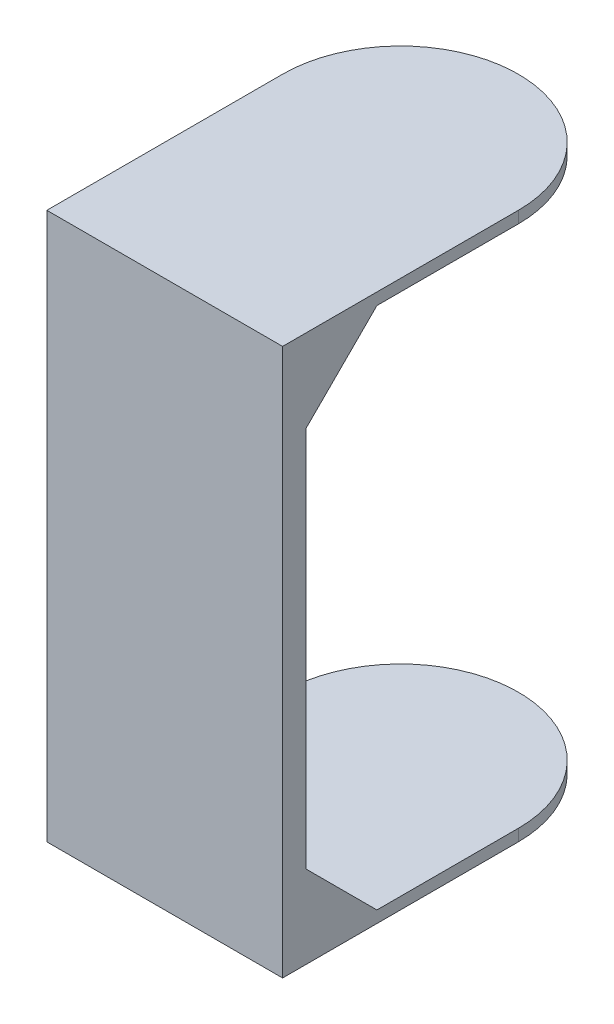
SolidWorks part; units mm, degrees
ref_plane "Front Plane" through (0, 0, 0) normal (0, 0, 1) x (1, 0, 0)
ref_plane "Top Plane" through (0, 0, 0) normal (0, 1, 0) x (1, 0, 0)
ref_plane "Right Plane" through (0, 0, 0) normal (1, 0, 0) x (0, 0, -1)
sketch "Plate Sketch" plane through (0, 0, 0) normal (0, 0, 1) x (1, 0, 0)
  line L1 (-50, 111) -> (50, 111)
  line L2 (-50, 111) -> (-50, -111)
  line L3 (-50, -111) -> (50, -111)
  line L4 (50, 111) -> (50, -111)
  line L5 (-50, 111) -> (50, -111) construction
  line L6 (-50, -111) -> (50, 111) construction
  point P0 (0, 0)
  dimension "D1" = 100
  dimension "D2" = 222
extrude "Plate Extrude" add sketch "Plate Sketch" against normal blind 10
sketch "Primary Support Sketch" plane through (50, 0, 0) normal (1, 0, 0) x (0, 0, -1)
  line L0 (10, 111) -> (10, 81)
  line L1 (10, 81) -> (40, 111)
  line L2 (40, 111) -> (10, 111)
  dimension "D1" = 30
extrude "Primary Support Extrude" add sketch "Primary Support Sketch" against normal blind 10
mirror "Primary Support Mirror" about plane through (0, 0, 0) normal (0, 1, 0) of "Primary Support Extrude"
sketch "Secondary Support Sketch" plane through (-50, 0, 0) normal (-1, 0, 0) x (0, 0, 1)
  line L0 (-10, 81) -> (-40, 111)
  line L3 (-40, 111) -> (-10, 111)
  line L4 (-10, 111) -> (-10, 81)
extrude "Secondary Support Extrude" add sketch "Secondary Support Sketch" against normal blind 10
sketch "Gripper Sketch" plane through (0, 111, 0) normal (0, 1, 0) x (1, 0, 0)
  line L0 (50, 100) -> (-50, 100) construction
  line L1 (0, 150) -> (0, 0) construction
  line L7 (-50, 0) -> (50, 0)
  line L8 (-50, 0) -> (-50, 100)
  line L9 (-50, 100) -> (50, 100) construction
  line L10 (50, 0) -> (50, 100)
  line L11 (-50, 0) -> (50, 100) construction
  line L12 (-50, 100) -> (50, 0) construction
  arc A0 (50, 100) -> (-50, 100) centre (0, 100) ccw
  point P5 (0, 150)
  point P6 (0, 50)
extrude "Gripper Extrude" add sketch "Gripper Sketch" along normal blind 5
mirror "Gripper Mirror" about plane through (0, 0, 0) normal (0, 1, 0) of "Gripper Extrude"
